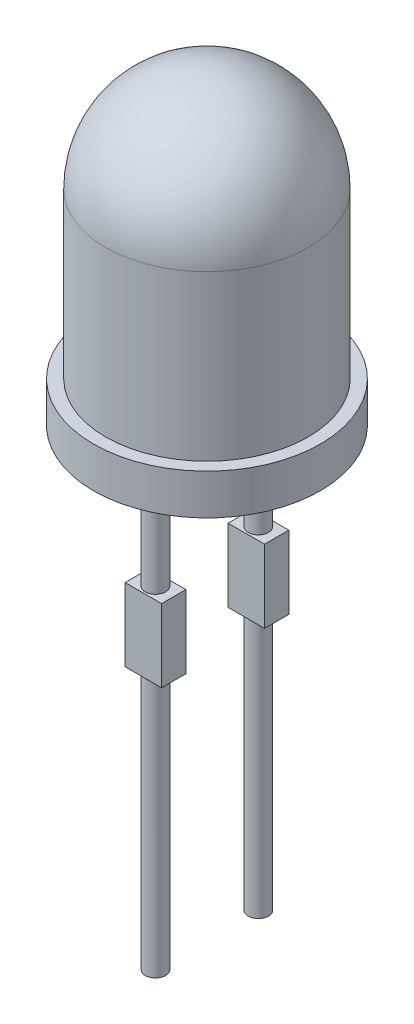
SolidWorks part; units mm, degrees
ref_plane "Front Plane" through (0, 0, 0) normal (0, 0, 1) x (1, 0, 0)
ref_plane "Top Plane" through (0, 0, 0) normal (0, 1, 0) x (1, 0, 0)
ref_plane "Right Plane" through (0, 0, 0) normal (1, 0, 0) x (0, 0, -1)
sketch "Sketch1" plane through (0, 0, 0) normal (1, 0, 0) x (0, 0, -1)
  line L0 (0, 4.525) -> (0, -10.9525) construction
  line L1 (-2.5, 2.025) -> (-2.5, -2.025)
  line L2 (-2.5, -2.025) -> (-2.8, -2.025)
  line L3 (-2.8, -2.025) -> (-2.8, -3.025)
  line L4 (-2.8, -3.025) -> (0, -3.025)
  line L5 (0, 4.525) -> (-4.2269, 4.525) construction
  line L6 (0, 4.525) -> (0, -3.025)
  arc A0 (-2.5, 2.025) -> (0, 4.525) centre (0, 2.025) cw
  point P11 (-2.5, 0)
  dimension "D1" = 5
  dimension "D2" = 7.55
  dimension "D3" = 1
  dimension "D4" = 5.6
revolve "Revolve1" add sketch "Sketch1" angle 360 about L0
sketch "Sketch2" plane through (0, -3.025, 0) normal (0, -1, 0) x (1, 0, 0)
  line L0 (0, 0) -> (3.908, 0) construction
  circle A0 centre (0, 1.27) radius 0.25
  circle A1 centre (0, -1.27) radius 0.25
  dimension "D1" = 2.54
  dimension "D2" = 0.5
extrude "Boss-Extrude1" add sketch "Sketch2" along normal blind 11 separate body
sketch "Sketch3" plane through (0, 0, 0) normal (1, 0, 0) x (0, 0, -1)
  line L0 (1.27, -3.025) -> (1.27, -15.6133) construction
  line L1 (0.97, -5.825) -> (1.57, -5.825)
  line L2 (0.97, -5.825) -> (0.97, -7.625)
  line L3 (0.97, -7.625) -> (1.57, -7.625)
  line L4 (1.57, -5.825) -> (1.57, -7.625)
  line L5 (0.97, -5.825) -> (1.57, -7.625) construction
  line L6 (0.97, -7.625) -> (1.57, -5.825) construction
  line L7 (1.52, -3.025) -> (1.02, -3.025) construction
  line L8 (-2.8, -3.025) -> (2.8, -3.025) construction
  line L9 (0, 0) -> (0, -3.6509) construction
  line L10 (-0.97, -7.625) -> (-1.57, -7.625)
  line L11 (-1.57, -5.825) -> (-1.57, -7.625)
  line L12 (-0.97, -5.825) -> (-1.57, -5.825)
  line L13 (-0.97, -5.825) -> (-0.97, -7.625)
  point P0 (1.27, -6.725)
  dimension "D1" = 0.6
  dimension "D2" = 2.8
  dimension "D3" = 1.8
extrude "Boss-Extrude2" add sketch "Sketch3" along normal mid plane 0.9
